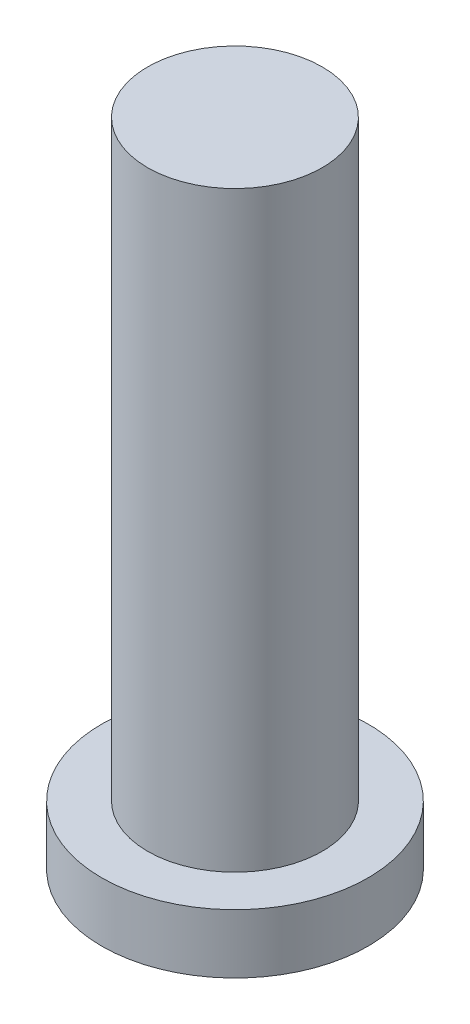
SolidWorks part; units mm, degrees
ref_plane "Front Plane" through (0, 0, 0) normal (0, 0, 1) x (1, 0, 0)
ref_plane "Top Plane" through (0, 0, 0) normal (0, 1, 0) x (1, 0, 0)
ref_plane "Right Plane" through (0, 0, 0) normal (1, 0, 0) x (0, 0, -1)
sketch "Sketch1" plane through (0, 0, 0) normal (0, 1, 0) x (1, 0, 0)
  circle A0 centre (0, 0) radius 4.5
extrude "Boss-Extrude1" add sketch "Sketch1" along normal blind 2
sketch "Sketch2" plane through (0, 2, 0) normal (0, 1, 0) x (1, 0, 0)
  circle A0 centre (0, 0) radius 2.95
extrude "Boss-Extrude4" add sketch "Sketch2" along normal blind 20
